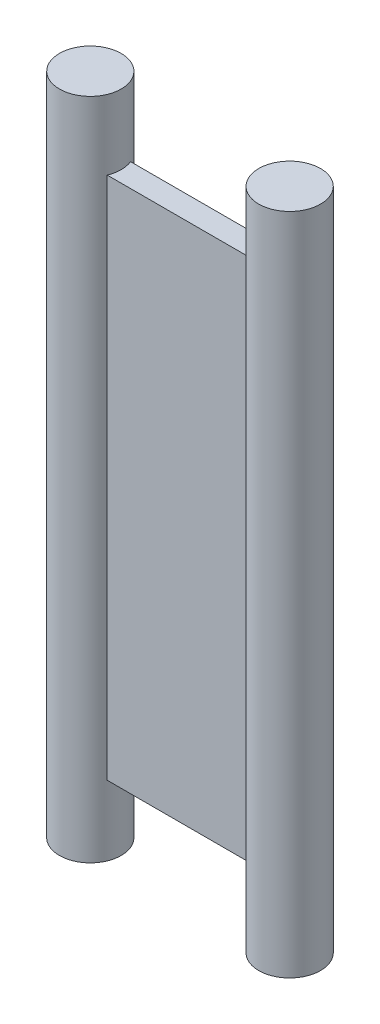
SolidWorks part; units mm, degrees
ref_plane "Front Plane" through (0, 0, 0) normal (0, 0, 1) x (1, 0, 0)
ref_plane "Top Plane" through (0, 0, 0) normal (0, 1, 0) x (1, 0, 0)
ref_plane "Right Plane" through (0, 0, 0) normal (1, 0, 0) x (0, 0, -1)
sketch "Sketch1" plane through (0, 0, 0) normal (0, 1, 0) x (1, 0, 0)
  line L1 (4.279, 0.5) -> (-4.279, 0.5)
  line L2 (4.279, 0.5) -> (4.279, -0.5)
  line L3 (4.279, -0.5) -> (-4.279, -0.5)
  line L4 (-4.279, 0.5) -> (-4.279, -0.5)
  line L5 (4.279, 0.5) -> (-4.279, -0.5) construction
  line L6 (4.279, -0.5) -> (-4.279, 0.5) construction
  point P0 (0, 0)
  dimension "D1" = 8.558
  dimension "D3" = 1
extrude "Boss-Extrude1" add sketch "Sketch1" along normal blind 22.5
ref_plane "Plane1" through (0, 11.25, 0) normal (0, 1, 0) x (1, 0, 0)
sketch "Sketch2" plane through (0, 11.25, 0) normal (0, 1, 0) x (1, 0, 0)
  line L0 (4.279, -0.5) -> (4.279, 0.5) construction
  line L1 (-4.279, 0.5) -> (-4.279, -0.5) construction
  line L2 (4.279, -0.5) -> (4.279, 0.5) construction
  line L3 (-4.279, 0.5) -> (-4.279, -0.5) construction
  circle A0 centre (-4.279, 0) radius 1.325
  circle A1 centre (4.279, 0) radius 1.325
  dimension "D1" = 2.65
extrude "Boss-Extrude2" add sketch "Sketch2" along normal mid plane 28.5
